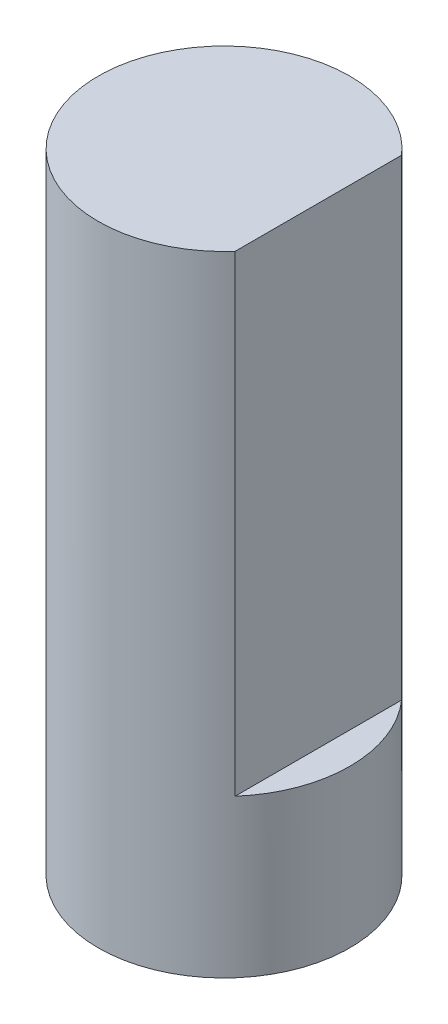
SolidWorks part; units mm, degrees
ref_plane "前视基准面" through (0, 0, 0) normal (0, 0, 1) x (1, 0, 0)
ref_plane "上视基准面" through (0, 0, 0) normal (0, 1, 0) x (1, 0, 0)
ref_plane "右视基准面" through (0, 0, 0) normal (1, 0, 0) x (0, 0, -1)
sketch "Sketch1" plane through (0, 0, 0) normal (0, 1, 0) x (1, 0, 0)
  circle A0 centre (0, 0) radius 4
  dimension "D1" = 8
extrude "Boss-Extrude1" add sketch "Sketch1" along normal blind 20
sketch "Sketch2" plane through (0, 20, 0) normal (0, 1, 0) x (1, 0, 0)
  line L0 (0, 4.1158) -> (0, -4.2529) construction
  line L1 (3, 2.6458) -> (3, -2.6458)
  line L3 (3, 4.1158) -> (3, -4.2529) construction
  arc A0 (3, -2.6458) -> (3, 2.6458) centre (0, 0) ccw
  dimension "D1" = 8
  dimension "D2" = 3
extrude "Cut-Extrude1" cut sketch "Sketch2" against normal blind 15
